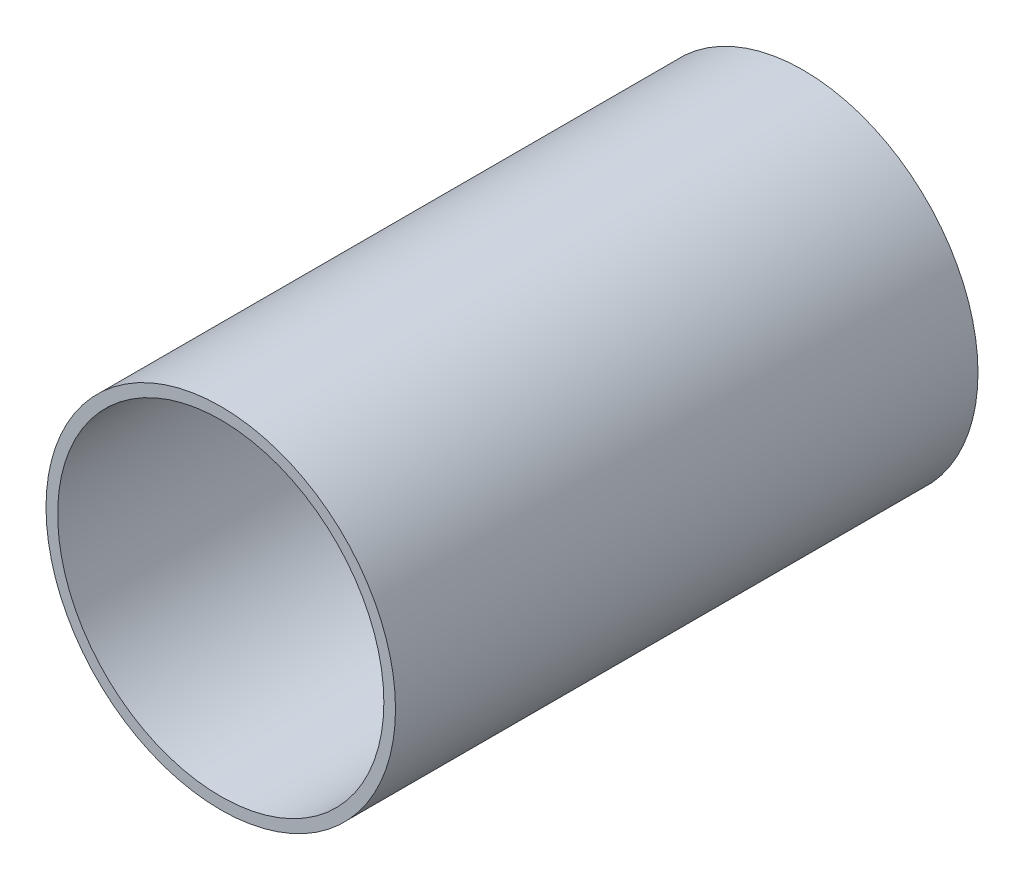
SolidWorks part; units mm, degrees
ref_plane "Front Plane" through (0, 0, 0) normal (0, 0, 1) x (1, 0, 0)
ref_plane "Top Plane" through (0, 0, 0) normal (0, 1, 0) x (1, 0, 0)
ref_plane "Right Plane" through (0, 0, 0) normal (1, 0, 0) x (0, 0, -1)
sketch "Sketch1" plane through (0, 0, 0) normal (0, 0, 1) x (1, 0, 0)
  circle A0 centre (0, 0) radius 45
  circle A1 centre (0, 0) radius 42
  dimension "D1" = 90
  dimension "D2" = 84
extrude "Boss-Extrude1" add sketch "Sketch1" along normal blind 150 contours A1
